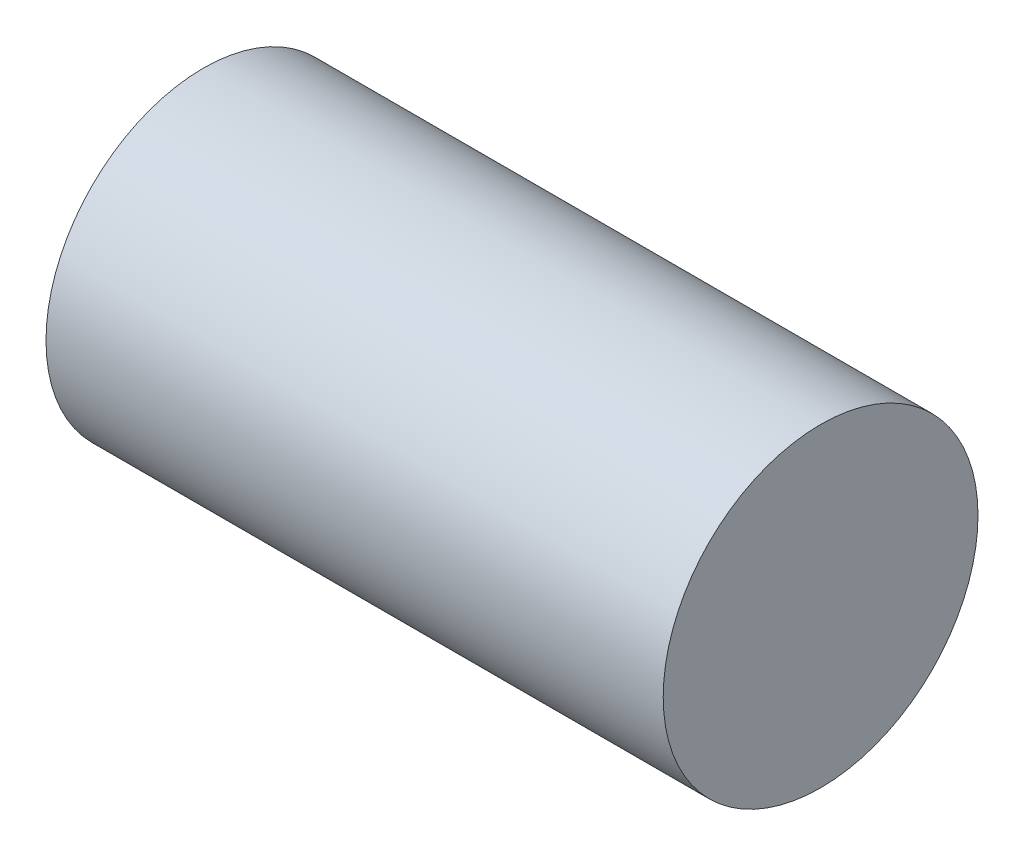
SolidWorks part; units mm, degrees
ref_plane "Front Plane" through (0, 0, 0) normal (0, 0, 1) x (1, 0, 0)
ref_plane "Top Plane" through (0, 0, 0) normal (0, 1, 0) x (1, 0, 0)
ref_plane "Right Plane" through (0, 0, 0) normal (1, 0, 0) x (0, 0, -1)
sketch "Sketch1" plane through (0, 0, 0) normal (1, 0, 0) x (0, 0, -1)
  circle A0 centre (0, 0) radius 6.477
  dimension "D1" = 12.954
extrude "Boss-Extrude1" add sketch "Sketch1" along normal blind 25.4
